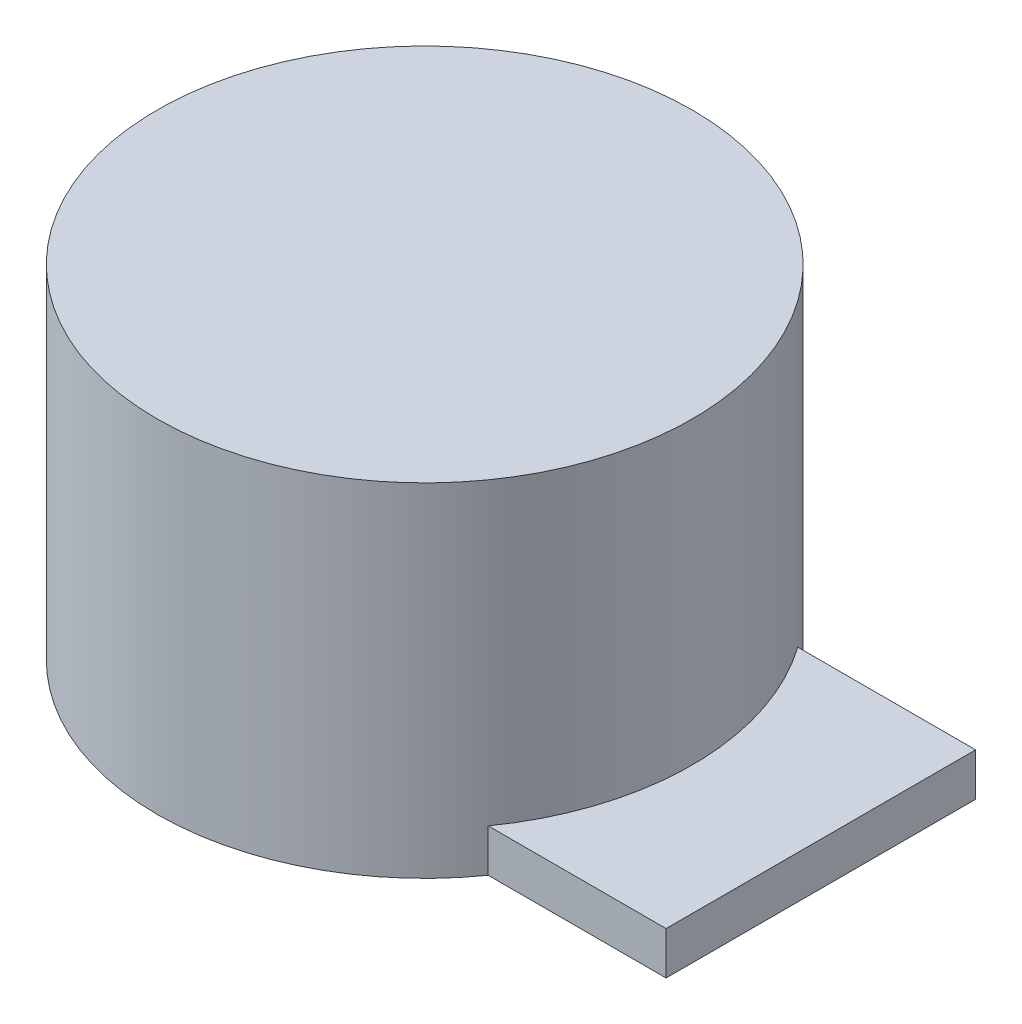
SolidWorks part; units mm, degrees
ref_plane "Front Plane" through (0, 0, 0) normal (0, 0, 1) x (1, 0, 0)
ref_plane "Top Plane" through (0, 0, 0) normal (0, 1, 0) x (1, 0, 0)
ref_plane "Right Plane" through (0, 0, 0) normal (1, 0, 0) x (0, 0, -1)
sketch "Sketch1" plane through (0, 0, 0) normal (0, 1, 0) x (1, 0, 0)
  circle A0 centre (0, 0) radius 15.875
  dimension "D1" = 31.75
extrude "Boss-Extrude1" add sketch "Sketch1" along normal blind 20.32
sketch "Sketch2" plane through (0, 0, 0) normal (0, -1, 0) x (1, 0, 0)
  line L1 (23.5014, 9.1826) -> (8.2486, 9.1826)
  line L2 (23.5014, 9.1826) -> (23.5014, -9.1826)
  line L3 (23.5014, -9.1826) -> (8.2486, -9.1826)
  line L4 (8.2486, 9.1826) -> (8.2486, -9.1826)
  line L5 (23.5014, 9.1826) -> (8.2486, -9.1826) construction
  line L6 (23.5014, -9.1826) -> (8.2486, 9.1826) construction
  circle A0 centre (0, 0) radius 15.875 construction
  point P0 (15.875, 0)
extrude "Boss-Extrude2" add sketch "Sketch2" against normal blind 2.54
